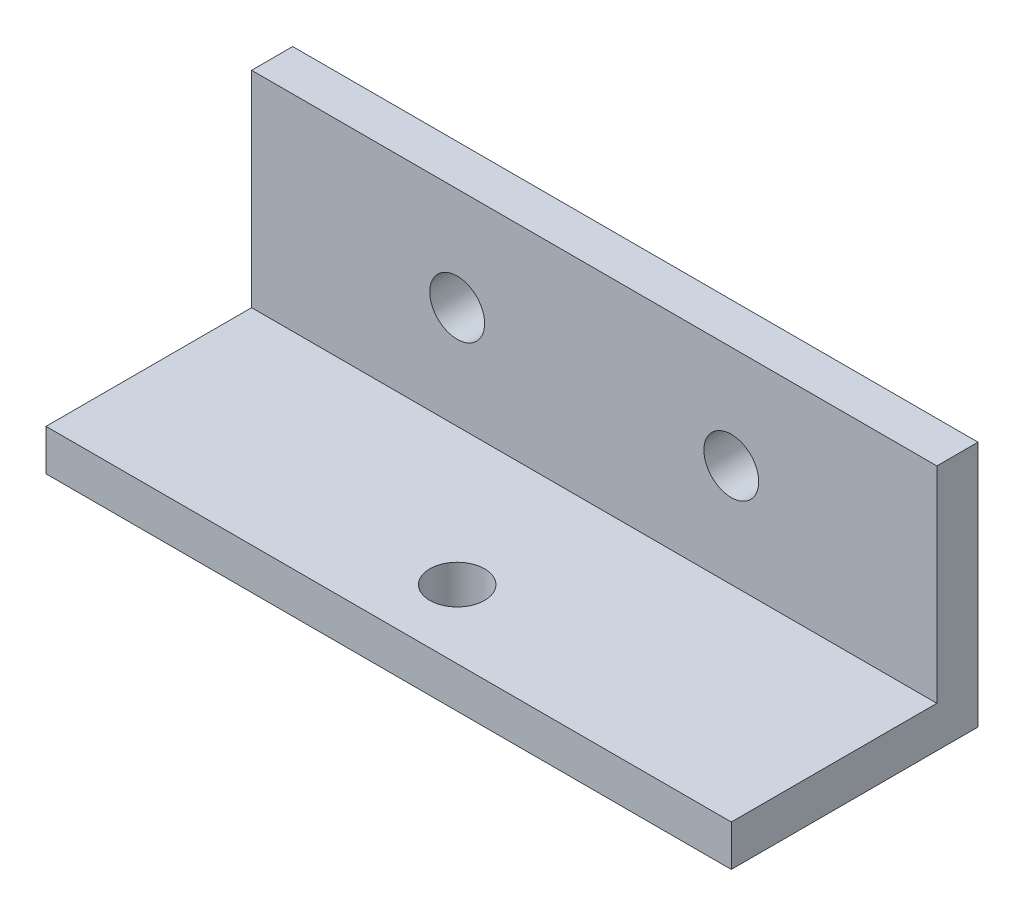
SolidWorks part; units mm, degrees
ref_plane "Front Plane" through (0, 0, 0) normal (0, 0, 1) x (1, 0, 0)
ref_plane "Top Plane" through (0, 0, 0) normal (0, 1, 0) x (1, 0, 0)
ref_plane "Right Plane" through (0, 0, 0) normal (1, 0, 0) x (0, 0, -1)
sketch "Sketch1" plane through (0, 0, 0) normal (0, 1, 0) x (1, 0, 0)
  line L1 (-25, -7.5) -> (25, -7.5)
  line L2 (-25, -7.5) -> (-25, 7.5)
  line L3 (-25, 7.5) -> (25, 7.5)
  line L4 (25, -7.5) -> (25, 7.5)
  line L5 (-25, -7.5) -> (25, 7.5) construction
  line L6 (-25, 7.5) -> (25, -7.5) construction
  circle A0 centre (0, -2.5) radius 2
  point P0 (0, 0)
  dimension "D3" = 4
  dimension "D1" = 50
  dimension "D2" = 15
  dimension "D4" = 10
extrude "Boss-Extrude1" add sketch "Sketch1" along normal blind 3
sketch "Sketch2" plane through (0, 0, 0) normal (0, -1, 0) x (1, 0, 0)
  line L0 (-25, -7.5) -> (-25, 7.5) construction
  line L1 (25, -7.5) -> (-25, -7.5)
  line L2 (25, -7.5) -> (25, -10.5)
  line L3 (25, -10.5) -> (-25, -10.5)
  line L4 (-25, -7.5) -> (-25, -10.5)
  dimension "D1" = 3
extrude "Boss-Extrude2" add sketch "Sketch2" against normal blind 18
sketch "Sketch3" plane through (0, 0, -7.5) normal (0, 0, 1) x (1, 0, 0)
  line L0 (0, 18) -> (0, 3) construction
  line L1 (25, 18) -> (-25, 18) construction
  line L2 (-25, 3) -> (25, 3) construction
  circle A0 centre (-10, 10.5) radius 2
  circle A1 centre (10, 10.5) radius 2
  dimension "D1" = 4
  dimension "D2" = 10
extrude "Cut-Extrude1" cut sketch "Sketch3" against normal blind 3
